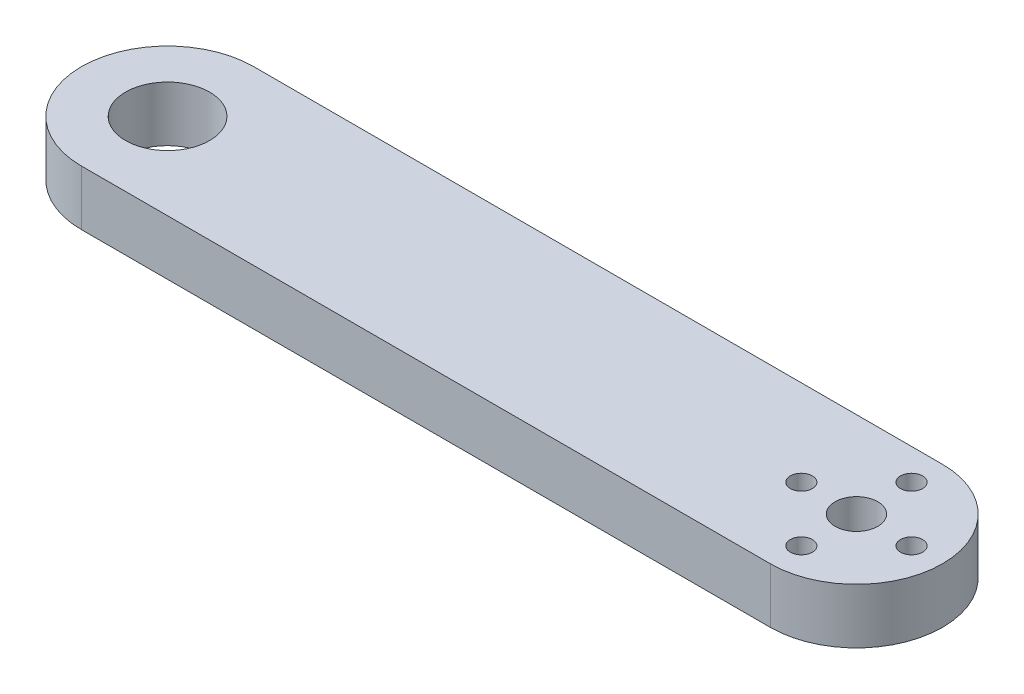
SolidWorks part; units mm, degrees
ref_plane "前视基准面" through (0, 0, 0) normal (0, 0, 1) x (1, 0, 0)
ref_plane "上视基准面" through (0, 0, 0) normal (0, 1, 0) x (1, 0, 0)
ref_plane "右视基准面" through (0, 0, 0) normal (1, 0, 0) x (0, 0, -1)
sketch "草图1" plane through (0, 0, 0) normal (0, 1, 0) x (1, 0, 0)
  line L0 (-50, 0) -> (50, 0) construction
  line L1 (-50, -12.5) -> (50, -12.5)
  line L2 (-50, -12.5) -> (-50, 12.5) construction
  line L3 (-50, 12.5) -> (50, 12.5)
  line L4 (50, -12.5) -> (50, 12.5) construction
  line L5 (-50, -12.5) -> (50, 12.5) construction
  line L6 (-50, 12.5) -> (50, -12.5) construction
  arc A0 (-50, 12.5) -> (-50, -12.5) centre (-50, 0) ccw
  arc A1 (50, 12.5) -> (50, -12.5) centre (50, 0) cw
  point P0 (0, 0)
  dimension "D1" = 25
  dimension "D2" = 100
extrude "凸台-拉伸1" add sketch "草图1" along normal blind 8
sketch "草图3" plane through (0, 8, 0) normal (0, 1, 0) x (1, 0, 0)
  circle A0 centre (-50, 0) radius 3.1
  circle A1 centre (50, 0) radius 8 construction
  circle A2 centre (50, 8) radius 1.6
  circle A3 centre (58, 0) radius 1.6
  circle A4 centre (50, -8) radius 1.6
  circle A5 centre (42, 0) radius 1.6
  circle A6 centre (50, 0) radius 3.1
  point P17 (50, 0)
  dimension "D1" = 6.2
  dimension "D2" = 16
  dimension "D4" = 3.2
  dimension "D5" = 6.2
  dimension "D3" = 4
extrude "切除-拉伸1" cut sketch "草图3" against normal through all
sketch "草图4" plane through (0, 8, 0) normal (0, 1, 0) x (1, 0, 0)
  circle A0 centre (-50, 0) radius 6.1
  dimension "D1" = 12.2
extrude "切除-拉伸2" cut sketch "草图4" against normal through all
